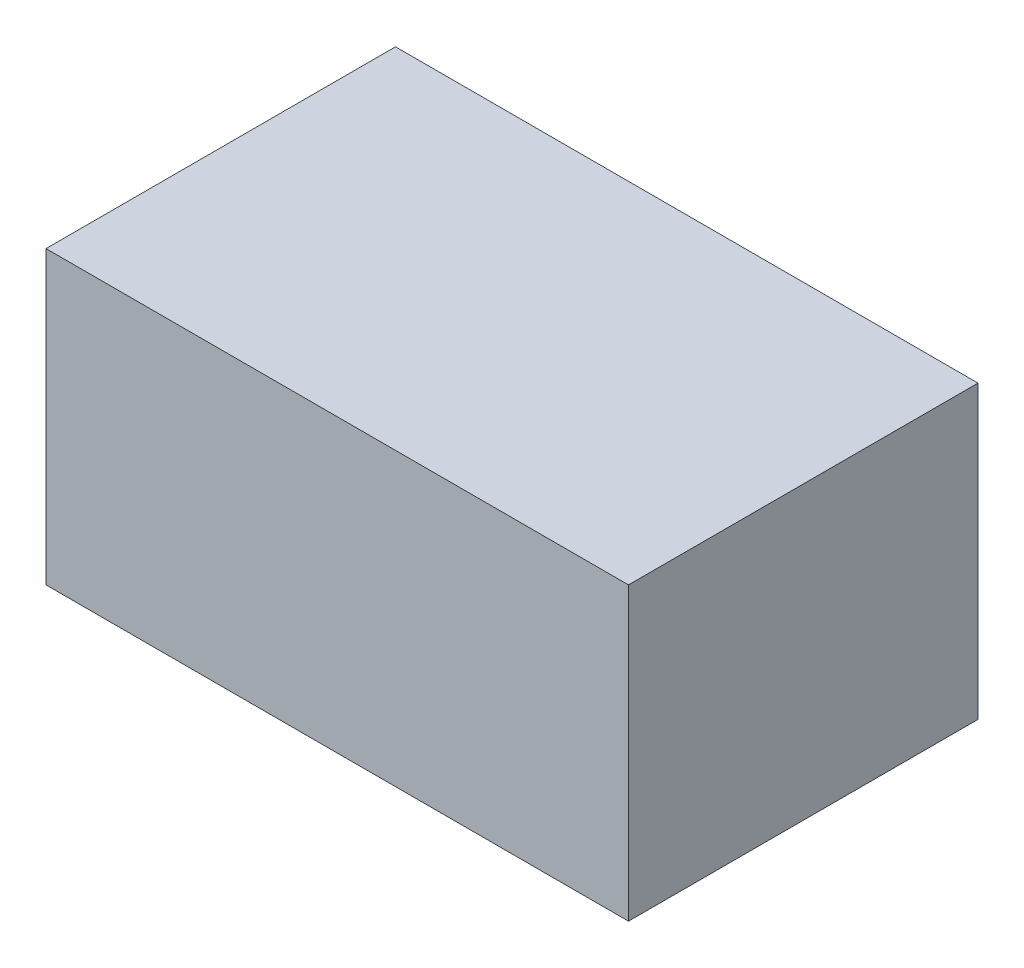
SolidWorks part; units mm, degrees
ref_plane "Front Plane" through (0, 0, 0) normal (0, 0, 1) x (1, 0, 0)
ref_plane "Top Plane" through (0, 0, 0) normal (0, 1, 0) x (1, 0, 0)
ref_plane "Right Plane" through (0, 0, 0) normal (1, 0, 0) x (0, 0, -1)
sketch "Sketch1" plane through (0, 0, 0) normal (0, 1, 0) x (1, 0, 0)
  line L1 (0, 0) -> (1, 0)
  line L2 (0, 0) -> (0, 0.6)
  line L3 (0, 0.6) -> (1, 0.6)
  line L4 (1, 0) -> (1, 0.6)
  dimension "D1" = 1
  dimension "D2" = 0.6
extrude "Boss-Extrude1" add sketch "Sketch1" along normal blind 0.5
